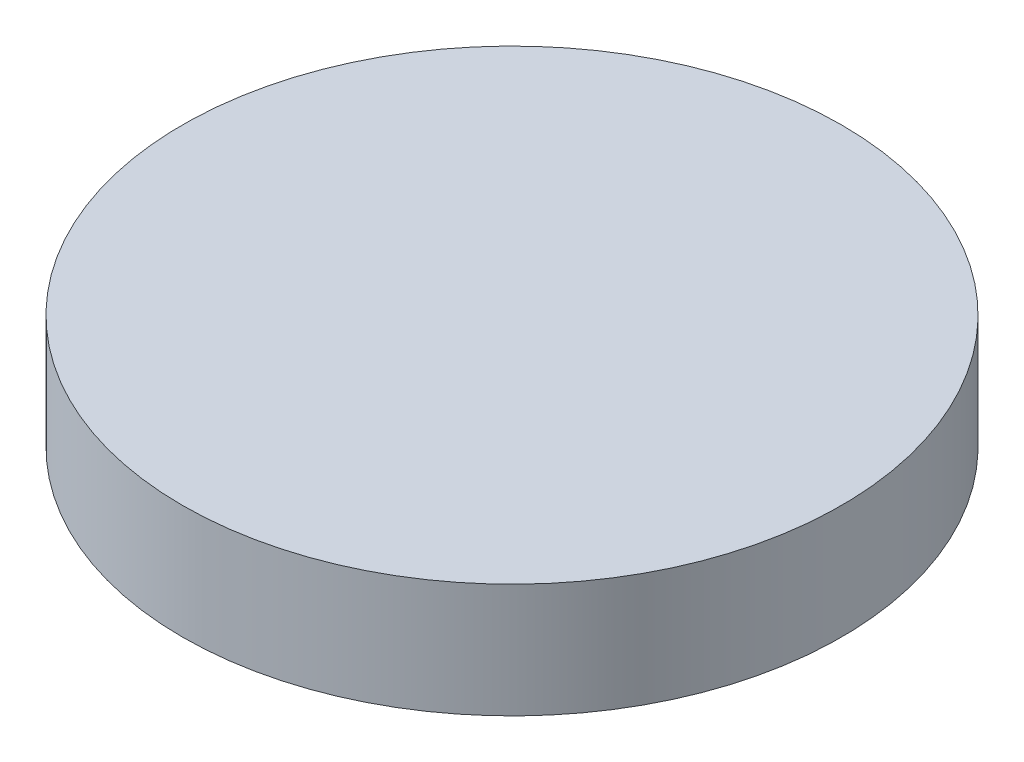
SolidWorks part; units mm, degrees
ref_plane "Front Plane" through (0, 0, 0) normal (0, 0, 1) x (1, 0, 0)
ref_plane "Top Plane" through (0, 0, 0) normal (0, 1, 0) x (1, 0, 0)
ref_plane "Right Plane" through (0, 0, 0) normal (1, 0, 0) x (0, 0, -1)
sketch "Sketch1" plane through (0, 0, 0) normal (0, 0, 1) x (1, 0, 0)
  line L0 (0, 750) -> (0, -2250) construction
  line L1 (0, -100) -> (650, -100)
  line L2 (0, -100) -> (0, 125)
  line L3 (0, 125) -> (650, 125)
  line L4 (650, -100) -> (650, 125)
  line L5 (0, -2250) -> (1000, -2250) construction
  line L6 (1000, -2250) -> (1000, 750) construction
  line L7 (1000, 750) -> (0, 750) construction
  dimension "D1" = 650
  dimension "D2" = 225
  dimension "D3" = 125
  dimension "D4" = 750
  dimension "D5" = 1000
  dimension "D6" = 3000
revolve "Revolve1" add sketch "Sketch1" angle 360 about L2
